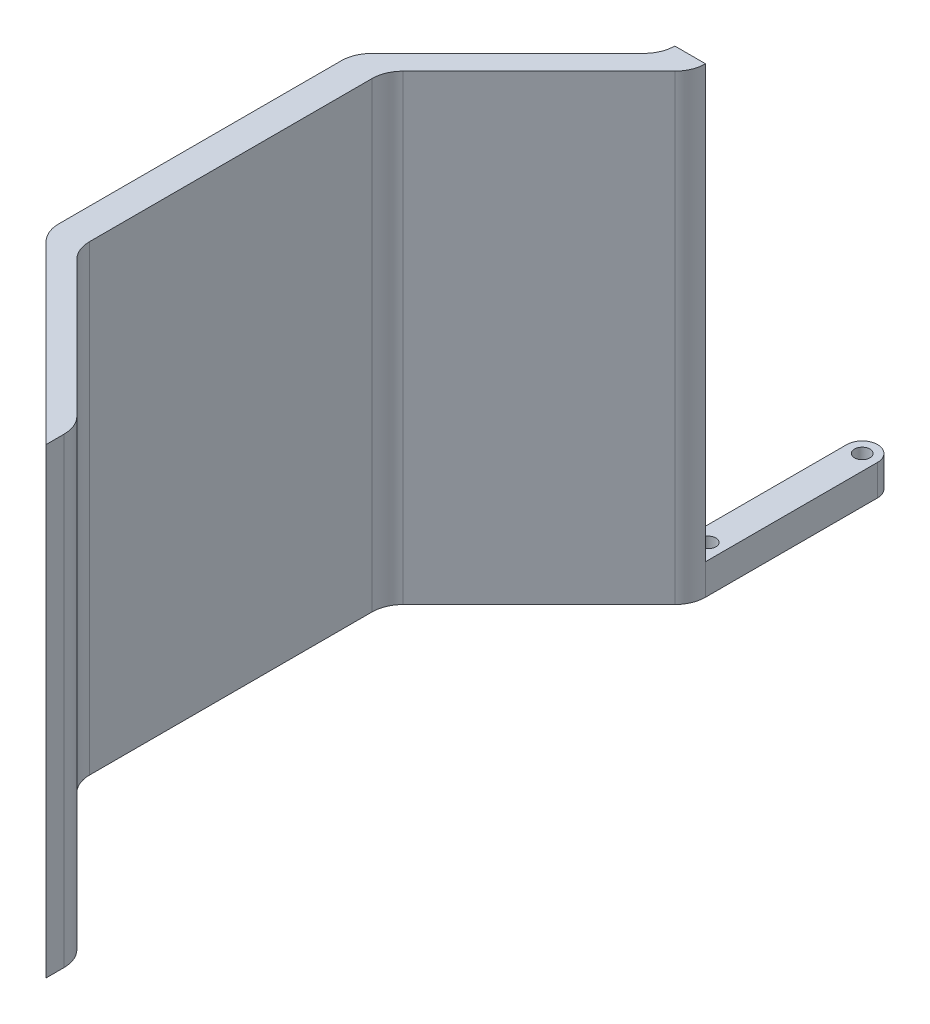
SolidWorks part; units mm, degrees
ref_plane "前视基准面" through (0, 0, 0) normal (0, 0, 1) x (1, 0, 0)
ref_plane "上视基准面" through (0, 0, 0) normal (0, 1, 0) x (1, 0, 0)
ref_plane "右视基准面" through (0, 0, 0) normal (1, 0, 0) x (0, 0, -1)
sketch "草图1" plane through (0, 0, 0) normal (0, 1, 0) x (1, 0, 0)
  line L0 (0, 0) -> (0, 100)
  line L1 (78.9294, 45.9986) -> (78.9294, -4.0014) construction
  line L2 (83.9294, 45.9986) -> (83.9294, -4.0014)
  line L3 (73.9294, 45.9986) -> (73.9294, -4.0014)
  line L4 (73.9294, -4.0014) -> (73.9294, -9.8592)
  line L5 (83.9294, -4.0014) -> (83.9294, -9.8592)
  line L8 (76.8583, -16.9303) -> (121.0004, -61.0725)
  line L9 (123.9294, -68.1435) -> (123.9294, -159.8592)
  line L12 (121.0004, -166.9303) -> (76.8583, -211.0725)
  line L13 (86.8583, -16.9303) -> (131.0004, -61.0725)
  line L14 (133.9294, -68.1435) -> (133.9294, -159.8592)
  line L15 (131.0004, -166.9303) -> (73.9294, -224.0014)
  line L16 (73.9294, -224.0014) -> (73.9294, -218.1435)
  line L17 (-73.9294, -224.0014) -> (-73.9294, -218.1435)
  line L18 (-121.0004, -166.9303) -> (-76.8583, -211.0725)
  line L19 (-131.0004, -166.9303) -> (-73.9294, -224.0014)
  line L20 (-133.9294, -68.1435) -> (-133.9294, -159.8592)
  line L21 (-123.9294, -68.1435) -> (-123.9294, -159.8592)
  line L22 (-86.8583, -16.9303) -> (-131.0004, -61.0725)
  line L23 (-76.8583, -16.9303) -> (-121.0004, -61.0725)
  line L24 (-83.9294, -4.0014) -> (-83.9294, -9.8592)
  line L25 (-73.9294, -4.0014) -> (-73.9294, -9.8592)
  line L26 (-83.9294, 45.9986) -> (-83.9294, -4.0014)
  line L27 (-73.9294, 45.9986) -> (-73.9294, -4.0014)
  arc A0 (83.9294, 45.9986) -> (73.9294, 45.9986) centre (78.9294, 45.9986) ccw
  arc A2 (73.9294, -218.1435) -> (76.8583, -211.0725) centre (83.9294, -218.1435) cw
  arc A3 (133.9294, -159.8592) -> (131.0004, -166.9303) centre (123.9294, -159.8592) cw
  arc A4 (123.9294, -159.8592) -> (121.0004, -166.9303) centre (113.9294, -159.8592) cw
  arc A5 (131.0004, -61.0725) -> (133.9294, -68.1435) centre (123.9294, -68.1435) cw
  arc A6 (123.9294, -68.1435) -> (121.0004, -61.0725) centre (113.9294, -68.1435) ccw
  arc A7 (86.8583, -16.9303) -> (83.9294, -9.8592) centre (93.9294, -9.8592) cw
  arc A8 (76.8583, -16.9303) -> (73.9294, -9.8592) centre (83.9294, -9.8592) cw
  arc A9 (-73.9294, -218.1435) -> (-76.8583, -211.0725) centre (-83.9294, -218.1435) ccw
  arc A10 (-133.9294, -159.8592) -> (-131.0004, -166.9303) centre (-123.9294, -159.8592) ccw
  arc A11 (-123.9294, -159.8592) -> (-121.0004, -166.9303) centre (-113.9294, -159.8592) ccw
  arc A12 (-131.0004, -61.0725) -> (-133.9294, -68.1435) centre (-123.9294, -68.1435) ccw
  arc A13 (-123.9294, -68.1435) -> (-121.0004, -61.0725) centre (-113.9294, -68.1435) cw
  arc A14 (-86.8583, -16.9303) -> (-83.9294, -9.8592) centre (-93.9294, -9.8592) ccw
  arc A15 (-76.8583, -16.9303) -> (-73.9294, -9.8592) centre (-83.9294, -9.8592) ccw
  arc A16 (-83.9294, 45.9986) -> (-73.9294, 45.9986) centre (-78.9294, 45.9986) cw
  point P5 (78.9294, 20.9986)
  dimension "D1" = 10
extrude "凸台-拉伸1" add sketch "草图1" along normal blind 150 contours A16 L26 L24 A14 L22 A12 L20 A10 L19 L17 A9 L18 A11 L21 A13 L23 A15 L25 L27
sketch "草图3" plane through (0, 150, 0) normal (0, 1, 0) x (1, 0, 0)
  line L0 (-83.9294, -9.8592) -> (-73.9294, -9.8592)
  line L1 (-73.9294, -9.8592) -> (-73.9294, 45.9986)
  line L3 (-83.9294, 45.9986) -> (-83.9294, -9.8592)
  arc A0 (-73.9294, 45.9986) -> (-83.9294, 45.9986) centre (-78.9294, 45.9986) ccw
extrude "切除-拉伸2" cut sketch "草图3" against normal blind 140
sketch "草图4" plane through (0, 0, 0) normal (0, -1, 0) x (1, 0, 0)
  circle A0 centre (-78.9294, -45.9986) radius 2.5
  circle A1 centre (-78.9294, 4.0014) radius 2.5
  point P5 (0, 0)
  point P6 (0, 0)
extrude "切除-拉伸3" cut sketch "草图4" against normal through all
